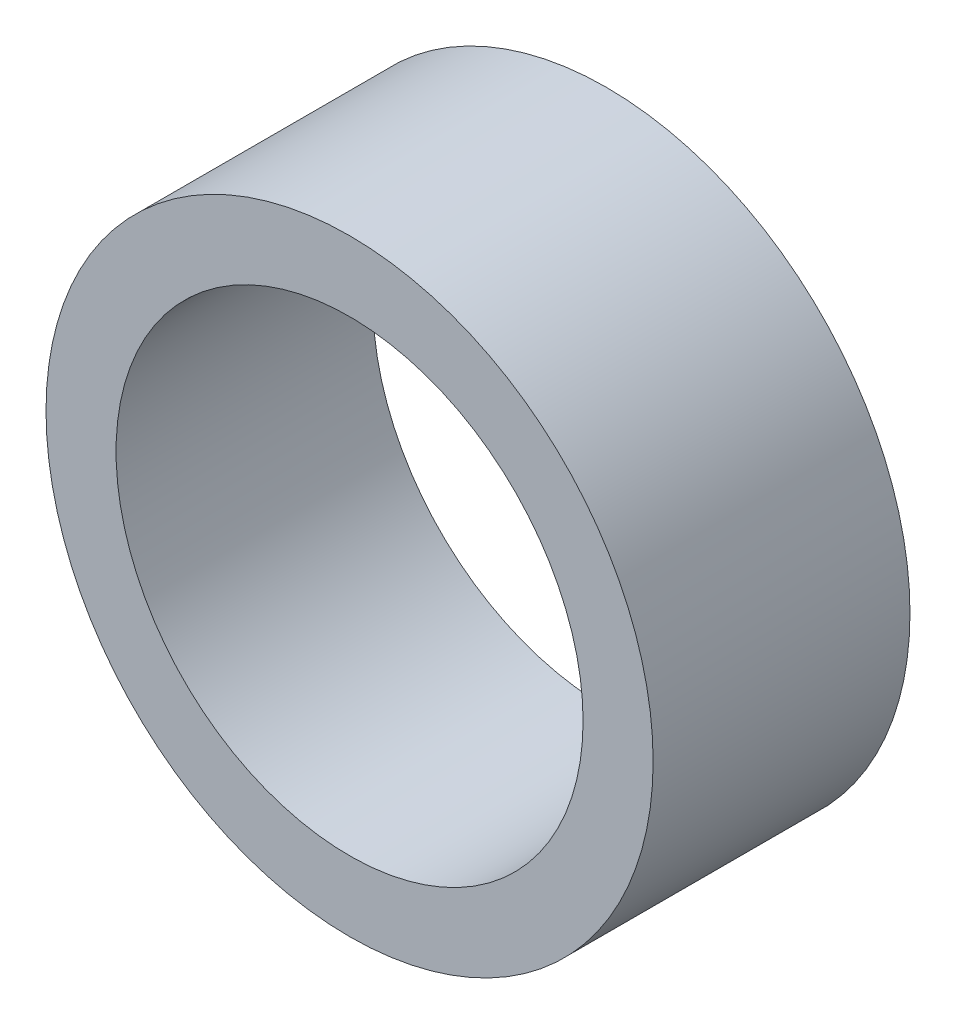
SolidWorks part; units mm, degrees
ref_plane "Ebene vorne" through (0, 0, 0) normal (0, 0, 1) x (1, 0, 0)
ref_plane "Ebene oben" through (0, 0, 0) normal (0, 1, 0) x (1, 0, 0)
ref_plane "Ebene rechts" through (0, 0, 0) normal (1, 0, 0) x (0, 0, -1)
sketch "Skizze1" plane through (0, 0, 0) normal (0, 0, 1) x (1, 0, 0)
  circle A0 centre (0, 0) radius 6.5
  circle A1 centre (0, 0) radius 5
  dimension "D1" = 13
  dimension "D2" = 10
extrude "Aufsatz-Linear austragen1" add sketch "Skizze1" along normal blind 5.5
